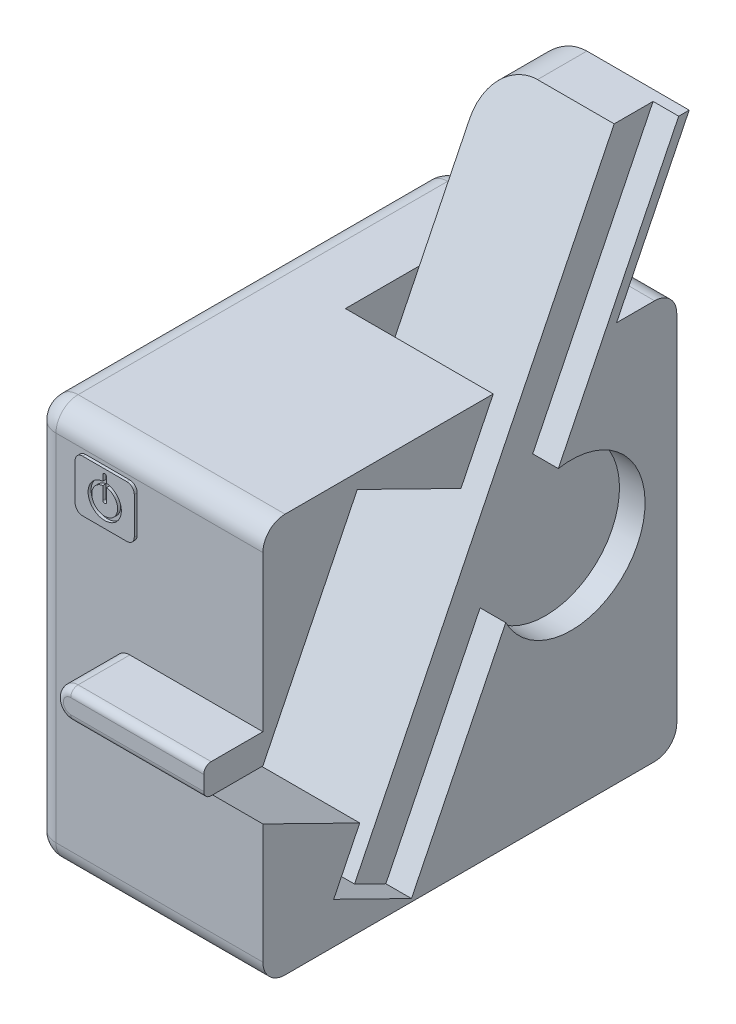
SolidWorks part; units mm, degrees
material "ABS"
ref_plane "Front" through (0, 0, 0) normal (0, 0, 1) x (1, 0, 0)
ref_plane "Top" through (0, 0, 0) normal (0, 1, 0) x (1, 0, 0)
ref_plane "Right" through (0, 0, 0) normal (1, 0, 0) x (0, 0, -1)
sketch "Sketch1" plane through (0, 0, 0) normal (0, 0, 1) x (1, 0, 0)
  line L0 (133.4483, 300.2587) -> (667.2416, 300.2587) construction
  line L2 (-196.85, 342.9) -> (196.85, 342.9)
  line L3 (-196.85, 342.9) -> (-196.85, 0)
  line L4 (-196.85, 0) -> (196.85, 0)
  line L5 (196.85, 342.9) -> (196.85, 0)
  dimension "D1" = 342.9
  dimension "D2" = 393.7
extrude "Boss-Extrude1" add sketch "Sketch1" along normal blind 355.6
sketch "Sketch2" plane through (0, 0, 355.6) normal (0, 0, 1) x (1, 0, 0)
  line L0 (196.85, 342.9) -> (-196.85, 342.9) construction
  line L1 (-158.75, 320.675) -> (-107.95, 320.675)
  line L2 (-158.75, 320.675) -> (-158.75, 276.225)
  line L3 (-158.75, 276.225) -> (-107.95, 276.225)
  line L4 (-107.95, 320.675) -> (-107.95, 276.225)
  line L5 (-158.75, 320.675) -> (-107.95, 276.225) construction
  line L6 (-158.75, 276.225) -> (-107.95, 320.675) construction
  line L7 (-196.85, 342.9) -> (-196.85, 0) construction
  point P0 (-133.35, 298.45)
  dimension "D1" = 44.45
  dimension "D2" = 63.5
  dimension "D3" = 44.45
  dimension "D4" = 50.8
extrude "Boss-Extrude2" add sketch "Sketch2" along normal blind 2.54
sketch "Sketch3" plane through (0, 0, 355.6) normal (0, 0, 1) x (1, 0, 0)
  line L0 (88.9, 298.45) -> (165.1, 298.45) construction
  line L1 (88.9, 307.975) -> (165.1, 307.975)
  line L2 (88.9, 288.925) -> (165.1, 288.925)
  line L5 (-107.95, 298.45) -> (88.9, 298.45) construction
  line L7 (-107.95, 276.225) -> (-107.95, 320.675) construction
  line L8 (196.85, 0) -> (196.85, 342.9) construction
  arc A0 (88.9, 307.975) -> (88.9, 288.925) centre (88.9, 298.45) ccw
  arc A1 (165.1, 288.925) -> (165.1, 307.975) centre (165.1, 298.45) ccw
  point P2 (127, 298.45)
  dimension "D1" = 19.05
  dimension "D2" = 76.2
  dimension "D3" = 31.75
extrude "Boss-Extrude3" add sketch "Sketch3" along normal blind 2.54
sketch "Sketch4" plane through (0, 0, 358.14) normal (0, 0, 1) x (1, 0, 0)
  line L0 (79.375, 298.45) -> (174.625, 298.45) construction
  arc A0 (88.9, 307.975) -> (88.9, 288.925) centre (88.9, 298.45) ccw construction
  arc A1 (165.1, 288.925) -> (165.1, 307.975) centre (165.1, 298.45) ccw construction
  circle A2 centre (92.075, 298.45) radius 3.81
  circle A3 centre (108.2865, 298.45) radius 3.81
  circle A4 centre (124.4979, 298.45) radius 3.81
  dimension "D1" = 7.62
  dimension "D2" = 16.2115
  dimension "D3" = 16.2115
  dimension "D4" = 12.7
extrude "Cut-Extrude1" cut sketch "Sketch4" against normal blind 2.54
sketch "Sketch5" plane through (0, 0, 355.6) normal (0, 0, 1) x (1, 0, 0)
  line L0 (-114.3, 177.8) -> (114.3, 177.8) construction
  line L1 (-114.3, 190.5) -> (114.3, 190.5)
  line L2 (-114.3, 165.1) -> (114.3, 165.1)
  line L3 (0, 177.8) -> (0, 342.9) construction
  line L4 (196.85, 342.9) -> (-196.85, 342.9) construction
  arc A0 (-114.3, 190.5) -> (-114.3, 165.1) centre (-114.3, 177.8) ccw
  arc A1 (114.3, 165.1) -> (114.3, 190.5) centre (114.3, 177.8) ccw
  point P2 (0, 177.8)
  dimension "D1" = 228.6
  dimension "D2" = 25.4
  dimension "D3" = 165.1
extrude "Boss-Extrude4" add sketch "Sketch5" along normal blind 50.8
fillet "Fillet1" radius 6.35 4 edges at (127, 177.8, 406.4) (0, 165.1, 406.4) (-127, 177.8, 406.4) (0, 190.5, 406.4)
fillet "Fillet2" radius 6.35 4 edges at (-158.75, 276.225, 356.87) (-107.95, 276.225, 356.87) (-107.95, 320.675, 356.87) (-158.75, 320.675, 356.87)
sketch "Sketch6" plane through (0, 0, 358.14) normal (0, 0, 1) x (1, 0, 0)
  line L0 (-133.35, 296.545) -> (-133.35, 276.225) construction
  line L3 (-133.35, 296.545) -> (-133.35, 315.595) construction
  line L4 (-134.9375, 296.545) -> (-134.9375, 315.595)
  line L5 (-131.7625, 296.545) -> (-131.7625, 315.595)
  line L6 (-152.4, 276.225) -> (-114.3, 276.225) construction
  circle A1 centre (-133.35, 296.545) radius 11.1125
  circle A2 centre (-133.35, 296.545) radius 14.2875
  arc A3 (-134.9375, 296.545) -> (-131.7625, 296.545) centre (-133.35, 296.545) ccw
  arc A4 (-131.7625, 315.595) -> (-134.9375, 315.595) centre (-133.35, 315.595) ccw
  point P12 (-133.35, 306.07)
  dimension "D2" = 22.225
  dimension "D3" = 3.175
  dimension "D4" = 19.05
  dimension "D5" = 20.32
  dimension "D1" = 3.175
extrude "Cut-Extrude2" cut sketch "Sketch6" against normal blind 2.54 contours L4 A2 L5 A1 | L5 A4 L4 A2 | L5 A2 L4 A1 | L4 A3 L5 A1
fillet "Fillet3" radius 19.05 12 edges at (-196.85, 171.45, 0) (-196.85, 171.45, 355.6) (196.85, 171.45, 0) (196.85, 171.45, 355.6) (0, 0, 0) (0, 0, 355.6) (0, 342.9, 0) (0, 342.9, 355.6) (-196.85, 342.9, 177.8) (196.85, 0, 177.8) (-196.85, 0, 177.8) (196.85, 342.9, 177.8)
sketch "Sketch7" plane through (0, 0, 0) normal (1, 0, 0) x (0, 0, -1)
  line L0 (-51.7276, 342.9) -> (10.6627, 469.9)
  line L1 (-336.55, 342.9) -> (-19.05, 342.9) construction
  line L2 (-94.1768, 342.9) -> (-31.7865, 469.9)
  line L3 (-31.7865, 469.9) -> (10.6627, 469.9)
  line L4 (-94.1768, 342.9) -> (-51.7276, 342.9)
  line L5 (0, 323.85) -> (0, 19.05) construction
  point P6 (0, 0)
  point P9 (0, 0)
  dimension "D1" = 38.1
  dimension "D2" = 127
  dimension "D3" = 94.1768
  dimension "D4" = 63.837
extrude "Boss-Extrude5" add sketch "Sketch7" along normal mid plane 254
fillet "Fillet4" radius 39.116 2 edges at (-127, 469.9, 10.5619) (127, 469.9, 10.5619)
sketch "Sketch8" plane through (0, 342.9, 0) normal (0, 1, 0) x (1, 0, 0)
  line L0 (0, -94.1768) -> (0, -125.9268) construction
  line L1 (127, -94.1768) -> (-127, -94.1768) construction
  line L3 (-127, -157.6768) -> (127, -157.6768)
  line L4 (-127, -157.6768) -> (-127, -94.1768)
  line L5 (-127, -94.1768) -> (127, -94.1768)
  line L6 (127, -157.6768) -> (127, -94.1768)
  line L7 (-127, -157.6768) -> (127, -94.1768) construction
  line L8 (-127, -94.1768) -> (127, -157.6768) construction
  dimension "D1" = 63.5
  dimension "D2" = 254
extrude "Cut-Extrude3" cut sketch "Sketch8" against normal blind 25.4
sketch "Sketch9" plane through (0, 0, 0) normal (1, 0, 0) x (0, 0, -1)
  line L1 (-912.7094, 769.4471) -> (-210.006, -1175.153)
  line L2 (-210.006, -1175.153) -> (1122.7154, 405.706)
  line L3 (1122.7154, 405.706) -> (-912.7094, 769.4471)
  circle A0 centre (0, 0) radius 596.8851 construction
extrude "Cut-Extrude4" cut sketch "Sketch9" along normal through all
sketch "Sketch10" plane through (0, 0, 0) normal (1, 0, 0) x (0, 0, -1)
  line L0 (-94.1768, 342.9) -> (-254.8643, 15.8091)
  line L1 (-157.6768, 342.9) -> (-185.414, 286.439)
  line L2 (-31.7865, 469.9) -> (-94.1768, 342.9) construction
  line L3 (-355.6, 165.1) -> (-274.4926, 330.2)
  line L5 (-355.6, 19.05) -> (-355.6, 165.1) construction
  line L7 (-355.6, 165.1) -> (-355.6, 121.8957)
  line L9 (-157.6768, 342.9) -> (-94.1768, 342.9)
  line L14 (-274.4926, 330.2) -> (-185.414, 286.439)
  line L15 (-355.6, 121.8957) -> (-268.5142, 299.1651) construction
  line L16 (-157.6768, 342.9) -> (-336.55, 342.9) construction
  line L17 (-355.6, 121.8957) -> (-272.3609, 81.0035)
  line L19 (-254.8643, 15.8091) -> (-294.7601, 35.4084)
  line L20 (-294.7601, 35.4084) -> (-272.3609, 81.0035)
  point P4 (-254.9286, 20.1401)
  dimension "D1" = 19.05
  dimension "D2" = 12.7
  dimension "D3" = 50.8
  dimension "D4" = 44.45
extrude "Cut-Extrude5" cut sketch "Sketch10" against normal blind 127
sketch "Sketch11" plane through (0, 0, 0) normal (1, 0, 0) x (0, 0, -1)
  line L0 (-94.1768, 342.9) -> (-106.6549, 317.5)
  line L1 (-106.6549, 317.5) -> (-94.1768, 317.5)
  line L2 (-94.1768, 317.5) -> (-94.1768, 342.9)
extrude "Boss-Extrude6" add sketch "Sketch11" against normal up to surface (127 mm away) up to face at (-127, 214.2414, 222.3434)
sketch "Sketch12" plane through (0, 103.9367, 211.5706) normal (0, 0.4409, 0.8975) x (1, 0, 0)
  line L0 (-127, -98.1877) -> (0, -98.1877) construction
  line L1 (0, 426.4566) -> (-22, 426.4566)
  line L2 (0, 426.4566) -> (0, -98.1877)
  line L3 (0, -98.1877) -> (-22, -98.1877)
  line L4 (-22, 426.4566) -> (-22, -98.1877)
  point P7 (0, 426.4566)
  dimension "D1" = 22
extrude "Cut-Extrude6" cut sketch "Sketch12" against normal blind 30
sketch "Sketch13" plane through (0, 0, 0) normal (1, 0, 0) x (0, 0, -1)
  line L0 (-90.7362, 196.8695) -> (0, 196.8695) construction
  line L1 (0, 19.05) -> (0, 323.85) construction
  line L2 (-90.7362, 196.8695) -> (-90.7362, 0) construction
  line L3 (-336.55, 0) -> (-19.05, 0) construction
  circle A0 centre (-90.7362, 196.8695) radius 63.5
  dimension "D3" = 127
  dimension "D1" = 196.8695
  dimension "D2" = 90.7362
extrude "Cut-Extrude7" cut sketch "Sketch13" against normal up to surface (22 mm away) up to face at (-22, 239.5476, 128.2377)
equation "\"D3@Sketch4\"=\"D2@Sketch4\""
